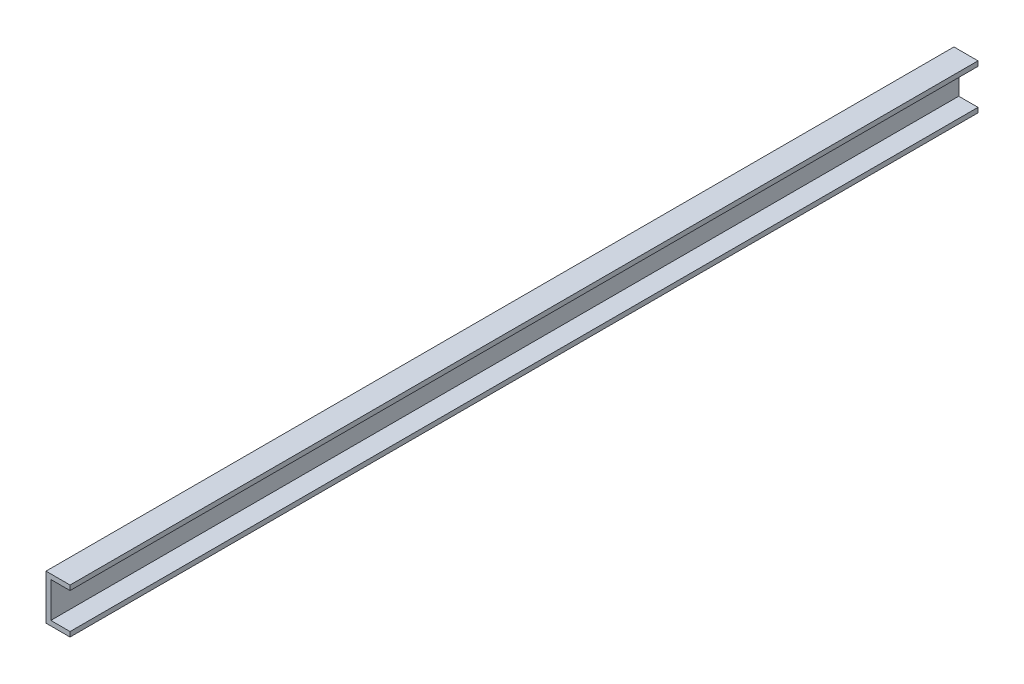
SolidWorks part; units mm, degrees
ref_plane "Front Plane" through (0, 0, 0) normal (0, 0, 1) x (1, 0, 0)
ref_plane "Top Plane" through (0, 0, 0) normal (0, 1, 0) x (1, 0, 0)
ref_plane "Right Plane" through (0, 0, 0) normal (1, 0, 0) x (0, 0, -1)
sketch "Sketch1" plane through (0, 0, 0) normal (0, 1, 0) x (1, 0, 0)
  line L0 (0, -755) -> (0, 755)
  point P4 (0, 0)
  dimension "D1" = 1510
sketch "Sketch2" plane through (0, 0, 0) normal (0, 0, 1) x (1, 0, 0)
  line L0 (0, -37.5) -> (0, 37.5)
  line L1 (0, 37.5) -> (40, 37.5)
  line L2 (40, 37.5) -> (40, 29.5)
  line L3 (40, 29.5) -> (8, 29.5)
  line L4 (8, 29.5) -> (8, -29.5)
  line L5 (8, -29.5) -> (40, -29.5)
  line L6 (40, -29.5) -> (40, -37.5)
  line L7 (40, -37.5) -> (0, -37.5)
  point P4 (0, 0)
  dimension "D1" = 75
  dimension "D2" = 8
  dimension "D3" = 40
  dimension "D4" = 8
other "C channel 80 X 8(1)"
ref_plane "Plane1" through (0, 0, 755) normal (0, 0, -1) x (-1, 0, 0)
sketch "Sketch11" plane through (0, 0, 755) normal (0, 0, -1) x (-1, 0, 0)
  line L8 (0, -37.5) -> (0, 37.5)
  line L9 (0, 37.5) -> (-40, 37.5)
  line L10 (-40, 37.5) -> (-40, 29.5)
  line L11 (-40, 29.5) -> (-8, 29.5)
  line L12 (-8, 29.5) -> (-8, -29.5)
  line L13 (-8, -29.5) -> (-40, -29.5)
  line L14 (-40, -29.5) -> (-40, -37.5)
  line L15 (-40, -37.5) -> (0, -37.5)
  line L16 (0, -37.5) -> (0, 37.5)
  line L17 (0, 37.5) -> (-40, 37.5)
  line L18 (-40, 37.5) -> (-40, 29.5)
  line L19 (-40, 29.5) -> (-8, 29.5)
  line L20 (-8, 29.5) -> (-8, -29.5)
  line L21 (-8, -29.5) -> (-40, -29.5)
  line L22 (-40, -29.5) -> (-40, -37.5)
  line L23 (-40, -37.5) -> (0, -37.5)
  dimension "D1" = 0
sketch "Sketch12" plane through (0, 37.5, 0) normal (0, 1, 0) x (1, 0, 0)
  line L0 (0, 755) -> (0, -755) construction
  line L1 (-72.0192, 0) -> (111.2262, 0) construction
  line L2 (0, -755) -> (40, -755) construction
  circle A0 centre (18, -545) radius 5
  circle A1 centre (18, -495) radius 5
  circle A2 centre (18, -80) radius 9
  dimension "D3" = 10
  dimension "D5" = 18
  dimension "D1" = 18
  dimension "D2" = 210
  dimension "D4" = 50
  dimension "D6" = 18
  dimension "D7" = 675
